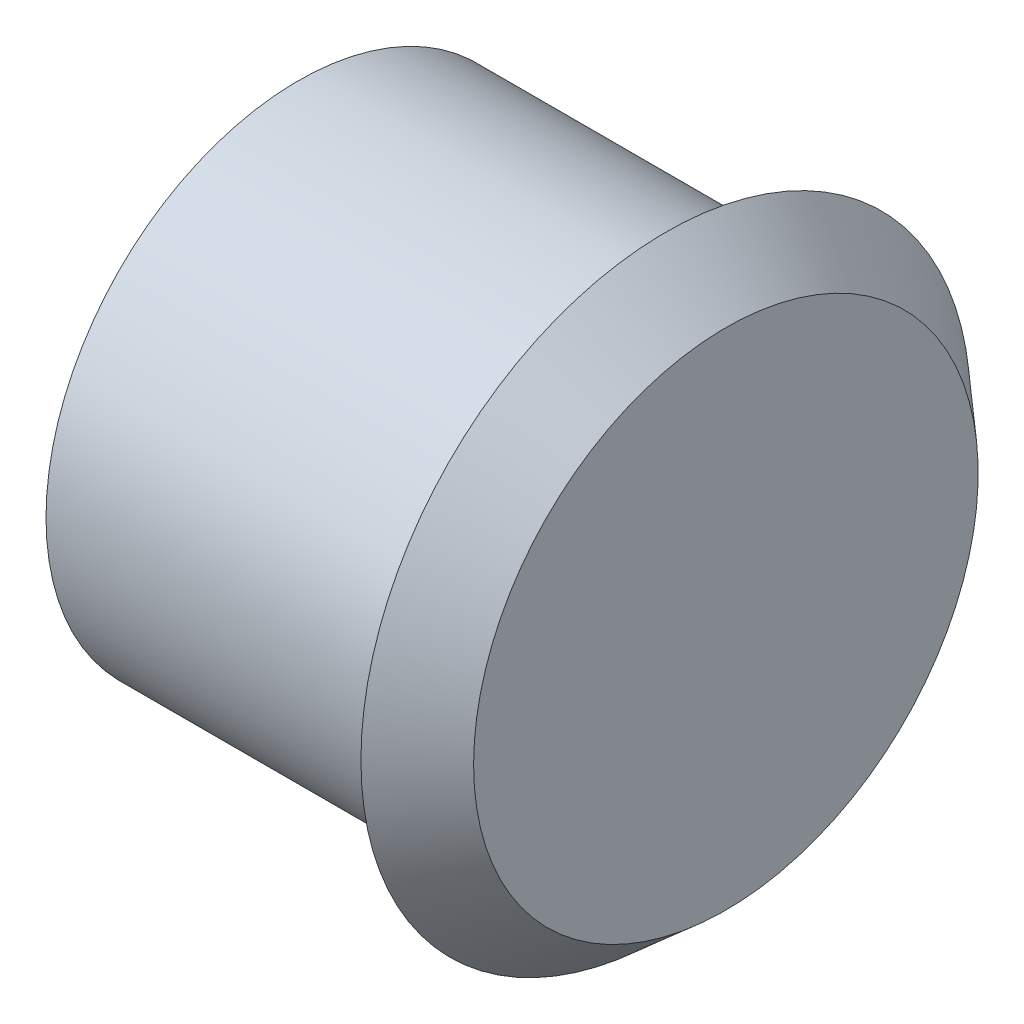
SolidWorks part; units mm, degrees
ref_plane "Front Plane" through (0, 0, 0) normal (0, 0, 1) x (1, 0, 0)
ref_plane "Top Plane" through (0, 0, 0) normal (0, 1, 0) x (1, 0, 0)
ref_plane "Right Plane" through (0, 0, 0) normal (1, 0, 0) x (0, 0, -1)
sketch "Sketch2" plane through (0, 0, 0) normal (0, 1, 0) x (1, 0, 0)
  line L0 (139.4574, -142.8532) -> (139.4574, -156.2245)
  line L1 (139.4574, -156.2245) -> (136.272, -159.0111)
  line L2 (136.272, -159.0111) -> (136.272, -142.8532)
  line L3 (136.272, -142.8532) -> (139.4574, -142.8532)
revolve "Revolve1" add sketch "Sketch2" angle 360 about L3
sketch "Sketch4" plane through (136.272, 0, 0) normal (-1, 0, 0) x (0, 0, 1)
  circle A0 centre (142.8532, 0) radius 13.3713
  circle A1 centre (142.8532, 0) radius 13.3713 construction
extrude "Boss-Extrude1" add sketch "Sketch4" along normal blind 19.4772
move or copy body "Body-Move/Copy1" [suppressed] bodies to move or copy 102
